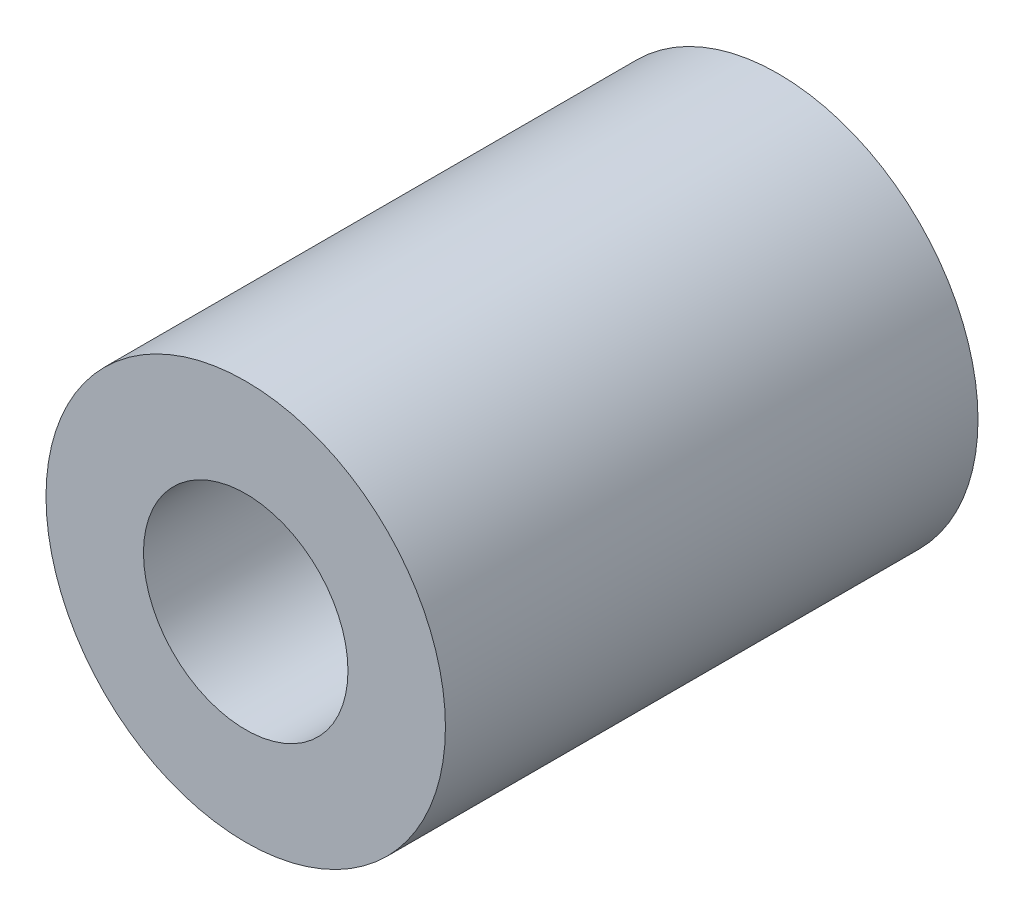
SolidWorks part; units mm, degrees
ref_plane "Front Plane" through (0, 0, 0) normal (0, 0, 1) x (1, 0, 0)
ref_plane "Top Plane" through (0, 0, 0) normal (0, 1, 0) x (1, 0, 0)
ref_plane "Right Plane" through (0, 0, 0) normal (1, 0, 0) x (0, 0, -1)
sketch "Sketch1" plane through (0, 0, 0) normal (0, 0, 1) x (1, 0, 0)
  circle A0 centre (0, 0) radius 4.7625
  circle A1 centre (0, 0) radius 2.4384
  dimension "OD" = 9.525
  dimension "ID" = 4.8768
extrude "Extrude1" add sketch "Sketch1" along normal mid plane 12.7
sketch "Sketch2" plane through (0, 0, 0) normal (1, 0, 0) x (0, 0, -1)
  line L0 (-6.35, -2.4384) -> (6.35, -2.4384) construction
  line L3 (6.35, 2.4384) -> (-6.35, 2.4384) construction
  line L5 (-6.35, -2.4384) -> (6.35, -2.4384)
  line L6 (6.35, 2.4384) -> (-6.35, 2.4384)
sketch "Sketch4" plane through (0, 0, 6.35) normal (0, 0, 1) x (1, 0, 0)
  line L0 (0, 0) -> (-1.7242, 1.7242)
  line L1 (0, -2.1828) -> (0, 2.1828) construction
  circle A0 centre (0, 0) radius 2.4384 construction
  dimension "D1" = 45
